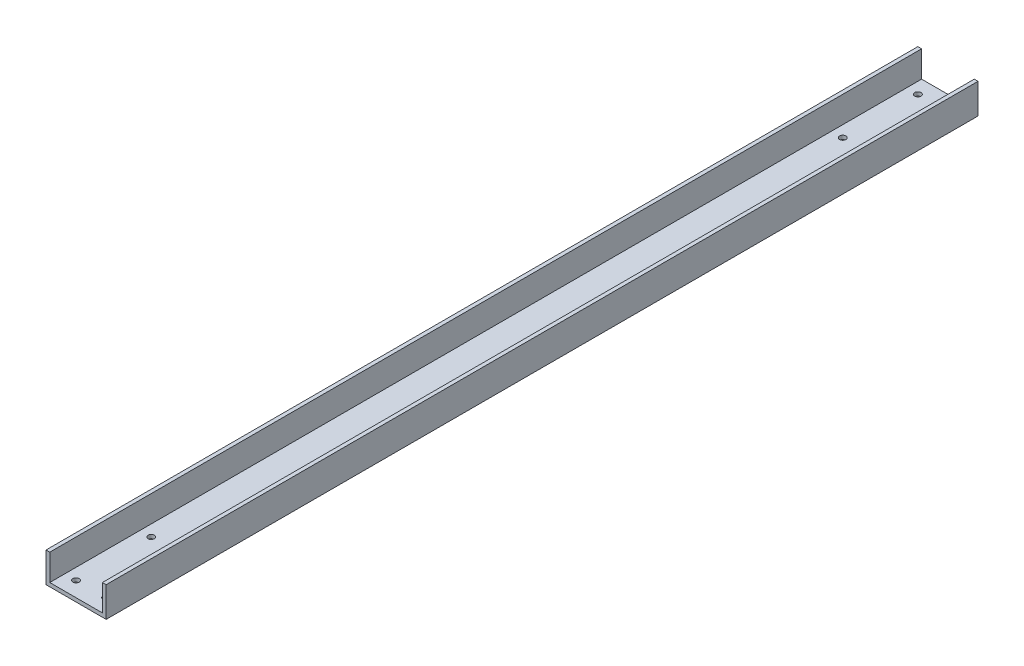
SolidWorks part; units mm, degrees
ref_plane "Front Plane" through (0, 0, 0) normal (0, 0, 1) x (1, 0, 0)
ref_plane "Top Plane" through (0, 0, 0) normal (0, 1, 0) x (1, 0, 0)
ref_plane "Right Plane" through (0, 0, 0) normal (1, 0, 0) x (0, 0, -1)
sketch "Sketch1" plane through (0, 0, 0) normal (0, 0, 1) x (1, 0, 0)
  line L0 (3.175, 3.175) -> (3.175, 25.4)
  line L1 (0, 0) -> (50.8, 0)
  line L2 (0, 0) -> (0, 25.4)
  line L3 (3.175, 3.175) -> (47.625, 3.175)
  line L4 (50.8, 0) -> (50.8, 25.4)
  line L5 (47.625, 3.175) -> (47.625, 25.4)
  line L6 (0, 25.4) -> (3.175, 25.4)
  line L7 (47.625, 25.4) -> (50.8, 25.4)
  dimension "D1" = 25.4
  dimension "D2" = 50.8
  dimension "D3" = 3.175
extrude "f" add sketch "Sketch1" along normal blind 736.6
sketch "Sketch2" plane through (0, 3.175, 0) normal (0, 1, 0) x (1, 0, 0)
  line L0 (15.5889, -736.6) -> (15.5889, -723.9) construction
  line L1 (12.7, -723.9) -> (38.1, -723.9) construction
  line L2 (12.7, -723.9) -> (12.7, -660.4) construction
  line L3 (12.7, -660.4) -> (38.1, -660.4) construction
  line L4 (38.1, -723.9) -> (38.1, -660.4) construction
  line L5 (12.7, -723.9) -> (38.1, -660.4) construction
  line L6 (12.7, -660.4) -> (38.1, -723.9) construction
  line L7 (47.625, -736.6) -> (3.175, -736.6) construction
  line L8 (3.175, -701.3254) -> (12.7, -701.3254) construction
  line L9 (3.175, -736.6) -> (3.175, 0) construction
  line L10 (38.1, -681.1466) -> (47.625, -681.1466) construction
  line L11 (47.625, -736.6) -> (47.625, 0) construction
  line L12 (3.175, -368.3) -> (47.625, -368.3) construction
  circle A0 centre (12.7, -723.9) radius 2.667
  circle A1 centre (12.7, -660.4) radius 2.667
  circle A2 centre (38.1, -660.4) radius 2.667
  circle A3 centre (38.1, -723.9) radius 2.667
  circle A4 centre (38.1, -12.7) radius 2.667
  circle A5 centre (38.1, -76.2) radius 2.667
  circle A6 centre (12.7, -12.7) radius 2.667
  circle A7 centre (12.7, -76.2) radius 2.667
  point P4 (25.4, -692.15)
  dimension "D4" = 5.334
  dimension "D1" = 25.4
  dimension "D2" = 63.5
  dimension "D3" = 12.7
extrude "Cut-Extrude1" cut sketch "Sketch2" against normal up to next
